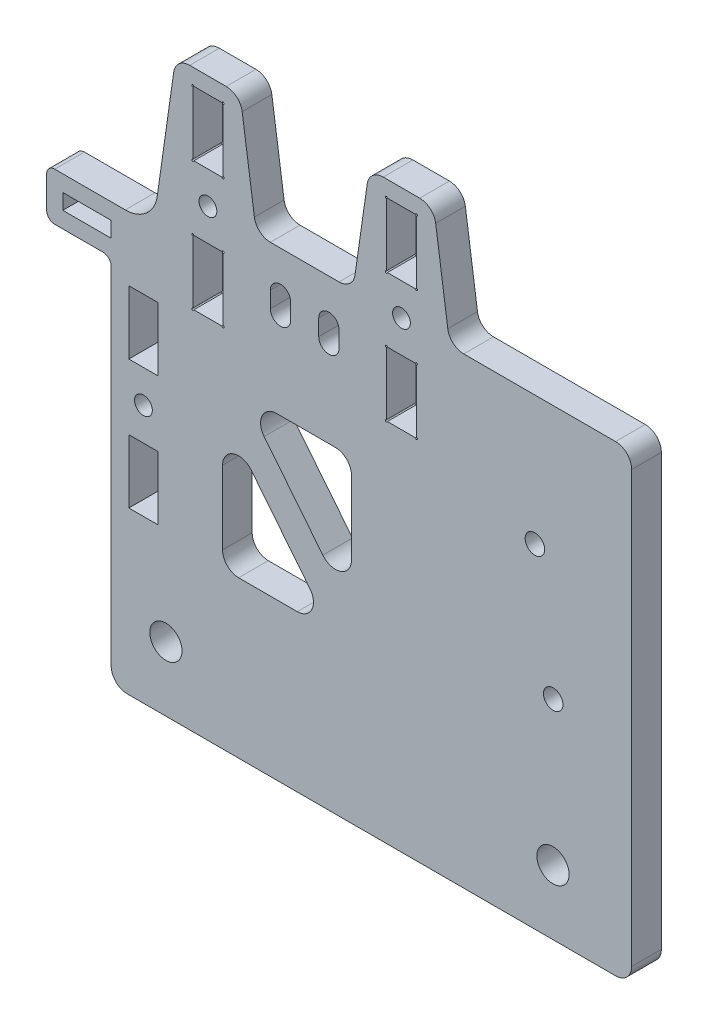
SolidWorks part; units mm, degrees
ref_plane "Front Plane" through (0, 0, 0) normal (0, 0, 1) x (1, 0, 0)
ref_plane "Top Plane" through (0, 0, 0) normal (0, 1, 0) x (1, 0, 0)
ref_plane "Right Plane" through (0, 0, 0) normal (1, 0, 0) x (0, 0, -1)
sketch "Sketch1" plane through (0, 0, 0) normal (0, 0, 1) x (1, 0, 0)
  line L0 (-40.2246, 5.8803) -> (-40.2246, -38.4697) construction
  line L1 (51.8504, -38.4697) -> (-46.5746, -38.4697)
  line L3 (-46.5746, 34.5553) -> (-46.5746, 52.6159)
  line L4 (-46.5746, -38.4697) -> (-46.5746, 34.5553)
  line L5 (51.8504, -38.4697) -> (-46.5746, 34.5553) construction
  line L6 (42.1271, 34.7961) -> (-46.5746, -38.4697) construction
  line L7 (-43.0956, -6.6197) -> (-37.3536, -6.6197)
  line L8 (-43.0956, 18.7803) -> (-37.3536, 18.7803)
  line L9 (-43.0956, 18.7803) -> (-43.0956, 31.2803)
  line L10 (-43.0956, 31.2803) -> (-37.3536, 31.2803)
  line L11 (-37.3536, 18.7803) -> (-37.3536, 31.2803)
  line L12 (-43.0956, 18.7803) -> (-37.3536, 31.2803) construction
  line L13 (-43.0956, 31.2803) -> (-37.3536, 18.7803) construction
  line L14 (-43.0956, -6.6197) -> (-43.0956, 5.8803)
  line L15 (-43.0956, 5.8803) -> (-37.3536, 5.8803)
  line L16 (-37.3536, -6.6197) -> (-37.3536, 5.8803)
  line L17 (-43.0956, -6.6197) -> (-37.3536, 5.8803) construction
  line L18 (-43.0956, 5.8803) -> (-37.3536, -6.6197) construction
  line L19 (-46.5746, 52.6159) -> (51.8504, 52.6159)
  line L20 (51.8504, -25.7697) -> (-46.5746, -25.7697) construction
  line L21 (-40.2246, -0.3697) -> (-40.2246, 25.0303) construction
  line L24 (51.8504, 52.6159) -> (55.8972, 52.6159)
  line L26 (51.8504, -38.4697) -> (55.8972, -38.4697)
  line L27 (55.8972, 52.6159) -> (55.8972, -38.4697)
  circle A0 centre (-35.7968, -25.7697) radius 3.175
  circle A1 centre (40.4032, -25.7697) radius 3.175
  circle A2 centre (-40.2246, 12.3303) radius 1.7526
  point P0 (0, 0)
  point P8 (-40.2246, 25.0303)
  point P14 (-40.2246, -0.3697)
  dimension "D10" = 6.35
  dimension "D13" = 3.5052
  dimension "D1" = 98.425
  dimension "D2" = 73.025
  dimension "D3" = 5.742
  dimension "D4" = 12.5
  dimension "D6" = 6.35
  dimension "D7" = 18.0606
  dimension "D8" = 15.494
  dimension "D12" = 10.7778
  dimension "D5" = 2
  dimension "D11" = 2
extrude "Boss-Extrude1" add sketch "Sketch1" along normal blind 5.842
sketch "Sketch2" plane through (0, 0, 5.842) normal (0, 0, 1) x (1, 0, 0)
  line L0 (55.8972, -38.4697) -> (55.8972, 52.6159) construction
  line L1 (-46.5746, -38.4697) -> (55.8972, -38.4697) construction
  line L2 (33.2912, 44.7153) -> (43.1972, 44.7153) construction
  line L3 (33.2912, -3.5447) -> (43.1972, -3.5447) construction
  line L4 (38.2442, -3.5447) -> (38.2442, 44.7153) construction
  line L6 (48.0747, 0.1423) -> (28.4136, 0.1423)
  line L7 (48.2732, 0.3408) -> (48.2732, 40.8299)
  line L8 (48.0747, 41.0283) -> (28.4136, 41.0283)
  line L9 (28.2152, 0.3408) -> (28.2152, 40.8299)
  line L10 (48.2732, 0.1423) -> (28.2152, 41.0283) construction
  line L11 (48.2732, 41.0283) -> (28.2152, 0.1423) construction
  circle A0 centre (43.1972, -3.5447) radius 1.7526
  circle A1 centre (33.2912, -3.5447) radius 1.7526
  circle A2 centre (43.1972, 44.7153) radius 1.7526
  circle A3 centre (33.2912, 44.7153) radius 1.7526
  arc A4 (48.0747, 0.1423) -> (48.2732, 0.3408) centre (48.2732, 0.1423) ccw
  arc A5 (48.2732, 40.8299) -> (48.0747, 41.0283) centre (48.2732, 41.0283) ccw
  arc A6 (28.2152, 40.8299) -> (28.4136, 41.0283) centre (28.2152, 41.0283) cw
  arc A7 (28.4136, 0.1423) -> (28.2152, 0.3408) centre (28.2152, 0.1423) cw
  point P14 (38.2442, 20.5853)
  dimension "D1" = 3.5052
  dimension "D6" = 0.3969
  dimension "D7" = 0.3969
  dimension "D2" = 12.7
  dimension "D3" = 34.925
  dimension "D4" = 20.058
  dimension "D5" = 40.886
extrude "Cut-Extrude1" [suppressed] cut sketch "Sketch2" against normal through all
sketch "Sketch3" plane through (0, 0, 5.842) normal (0, 0, 1) x (1, 0, 0)
  line L0 (-46.5746, 39.9159) -> (55.8972, 39.9159) construction
  line L1 (-46.5746, 52.6159) -> (-46.5746, -38.4697) construction
  line L2 (55.8972, -38.4697) -> (55.8972, 52.6159) construction
  line L3 (55.8972, 52.6159) -> (-46.5746, 52.6159) construction
  line L4 (7.5909, 46.2659) -> (13.5599, 33.5659) construction
  line L5 (-24.7385, 33.5659) -> (-30.3106, 33.5659)
  line L6 (-24.5401, 33.7644) -> (-24.5401, 46.0675)
  line L7 (-24.7385, 46.2659) -> (-30.3106, 46.2659)
  line L8 (-30.5091, 33.7644) -> (-30.5091, 46.0675)
  line L9 (-24.5401, 33.5659) -> (-30.5091, 46.2659) construction
  line L10 (-8.4746, 52.6159) -> (-8.4746, 39.9159) construction
  line L11 (-24.5401, 46.2659) -> (-30.5091, 33.5659) construction
  line L12 (7.5909, 33.5659) -> (13.5599, 46.2659) construction
  line L13 (13.5599, 33.7644) -> (13.5599, 46.0675)
  line L14 (7.7894, 46.2659) -> (13.3615, 46.2659)
  line L15 (7.5909, 33.7644) -> (7.5909, 46.0675)
  line L16 (7.7894, 33.5659) -> (13.3615, 33.5659)
  arc A0 (-24.7385, 33.5659) -> (-24.5401, 33.7644) centre (-24.5401, 33.5659) ccw
  arc A1 (-30.5091, 33.7644) -> (-30.3106, 33.5659) centre (-30.5091, 33.5659) ccw
  arc A2 (-24.7385, 46.2659) -> (-24.5401, 46.0675) centre (-24.5401, 46.2659) cw
  arc A3 (-30.5091, 46.0675) -> (-30.3106, 46.2659) centre (-30.5091, 46.2659) cw
  arc A4 (13.5599, 46.0675) -> (13.3615, 46.2659) centre (13.5599, 46.2659) ccw
  arc A5 (7.7894, 46.2659) -> (7.5909, 46.0675) centre (7.5909, 46.2659) ccw
  arc A6 (13.5599, 33.7644) -> (13.3615, 33.5659) centre (13.5599, 33.5659) cw
  arc A7 (7.7894, 33.5659) -> (7.5909, 33.7644) centre (7.5909, 33.5659) cw
  point P6 (-27.5246, 39.9159)
  point P7 (-27.5246, 39.9159)
  point P39 (10.5754, 39.9159)
  dimension "D3" = 0.3969
  dimension "D4" = 0.3969
  dimension "D1" = 5.969
  dimension "D2" = 12.7
  dimension "D5" = 12.7
  dimension "D6" = 19.05
  dimension "D9" = 19.05
extrude "Cut-Extrude2" cut sketch "Sketch3" against normal through all
sketch "Sketch4" plane through (0, 0, 5.842) normal (0, 0, 1) x (1, 0, 0)
  line L0 (-30.5091, 39.9159) -> (13.5599, 39.9159) construction
  line L3 (10.5754, 39.9159) -> (10.5754, 65.3159) construction
  line L4 (-8.4746, 39.9159) -> (-8.4746, 46.2659) construction
  line L5 (1.0366, 52.6159) -> (4.2254, 74.8409)
  line L6 (13.3615, 71.6659) -> (7.7894, 71.6659)
  line L7 (13.5599, 71.4675) -> (13.5599, 59.1644)
  line L8 (13.3615, 58.9659) -> (7.7894, 58.9659)
  line L9 (7.5909, 71.4675) -> (7.5909, 59.1644)
  line L10 (13.5599, 71.6659) -> (7.5909, 58.9659) construction
  line L11 (13.5599, 58.9659) -> (7.5909, 71.6659) construction
  line L12 (55.8972, 52.6159) -> (-46.5746, 52.6159) construction
  line L13 (4.2254, 74.8409) -> (16.9254, 74.8409)
  line L14 (16.9254, 74.8409) -> (20.0866, 52.6159)
  line L15 (20.0866, 52.6159) -> (1.0366, 52.6159)
  line L16 (-30.5091, 58.9659) -> (-24.5401, 71.6659) construction
  line L17 (-30.5091, 71.6659) -> (-24.5401, 58.9659) construction
  line L18 (-37.0358, 52.6159) -> (-17.9858, 52.6159)
  line L19 (-33.8746, 74.8409) -> (-37.0358, 52.6159)
  line L20 (-21.1746, 74.8409) -> (-33.8746, 74.8409)
  line L21 (-24.5401, 71.4675) -> (-24.5401, 59.1644)
  line L22 (-30.3106, 58.9659) -> (-24.7385, 58.9659)
  line L23 (-30.5091, 71.4675) -> (-30.5091, 59.1644)
  line L24 (-30.3106, 71.6659) -> (-24.7385, 71.6659)
  line L25 (-17.9858, 52.6159) -> (-21.1746, 74.8409)
  line L26 (13.5599, 33.7644) -> (13.5599, 46.0675) construction
  line L27 (-30.5091, 46.0675) -> (-30.5091, 33.7644) construction
  arc A0 (13.5599, 71.4675) -> (13.3615, 71.6659) centre (13.5599, 71.6659) ccw
  arc A1 (13.3615, 58.9659) -> (13.5599, 59.1644) centre (13.5599, 58.9659) ccw
  arc A2 (7.7894, 58.9659) -> (7.5909, 59.1644) centre (7.5909, 58.9659) cw
  arc A3 (7.5909, 71.4675) -> (7.7894, 71.6659) centre (7.5909, 71.6659) cw
  arc A4 (-24.5401, 71.4675) -> (-24.7385, 71.6659) centre (-24.5401, 71.6659) ccw
  arc A5 (-30.5091, 71.4675) -> (-30.3106, 71.6659) centre (-30.5091, 71.6659) cw
  arc A6 (-24.7385, 58.9659) -> (-24.5401, 59.1644) centre (-24.5401, 58.9659) ccw
  arc A7 (-30.3106, 58.9659) -> (-30.5091, 59.1644) centre (-30.5091, 58.9659) cw
  point P20 (10.5754, 74.8409)
  point P29 (-27.5246, 74.8409)
  dimension "D7" = 0.3969
  dimension "D8" = 0.3969
  dimension "D1" = 25.4
  dimension "D2" = 12.7
  dimension "D3" = 5.969
  dimension "D4" = 9.525
  dimension "D5" = 12.7
  dimension "D6" = 19.05
extrude "Boss-Extrude2" add sketch "Sketch4" against normal up to surface (5.842 mm away) up to face at (10.5754, 39.9159, 0)
fillet "Fillet1" radius 3.175 7 edges at (16.9254, 74.8409, 2.921) (4.2254, 74.8409, 2.921) (-17.9858, 52.6159, 2.921) (-21.1746, 74.8409, 2.921) (-33.8746, 74.8409, 2.921)
sketch "Sketch5" plane through (0, 0, 5.842) normal (0, 0, 1) x (1, 0, 0)
  line L0 (-27.5246, 71.6659) -> (-27.5246, 33.5659) construction
  line L1 (-24.7385, 71.6659) -> (-30.3106, 71.6659) construction
  line L2 (-30.3106, 33.5659) -> (-24.7385, 33.5659) construction
  line L3 (10.5754, 71.6659) -> (10.5754, 33.5659) construction
  line L4 (13.3615, 71.6659) -> (7.7894, 71.6659) construction
  line L5 (7.7894, 33.5659) -> (13.3615, 33.5659) construction
  circle A0 centre (-27.5246, 52.6159) radius 1.7526
  circle A1 centre (10.5754, 52.6159) radius 1.7526
  dimension "D1" = 3.5052
  dimension "D2" = 3.5052
extrude "Cut-Extrude3" cut sketch "Sketch5" against normal through all
sketch "Sketch6" plane through (0, 0, 5.842) normal (0, 0, 1) x (1, 0, 0)
  line L0 (-37.0358, 52.6159) -> (-39.1672, 37.6303)
  line L1 (-34.2626, 72.113) -> (-37.0358, 52.6159) construction
  line L2 (-37.3536, 31.2803) -> (-43.0956, 31.2803) construction
  line L3 (-39.1672, 37.6303) -> (-46.5746, 37.6303)
  line L4 (-46.5746, 52.6159) -> (-46.5746, -38.4697) construction
  line L5 (-46.5746, 37.6303) -> (-46.5746, 52.6159)
  line L6 (-46.5746, 52.6159) -> (-37.0358, 52.6159)
  dimension "D1" = 6.35
extrude "Cut-Extrude4" cut sketch "Sketch6" against normal through all
fillet "Fillet2" radius 3.175 5 edges at (-39.1672, 37.6303, 2.921) (-46.5746, 37.6303, 2.921) (-46.5746, -38.4697, 2.921) (55.8972, 52.6159, 2.921) (55.8972, -38.4697, 2.921)
sketch "Sketch7" [suppressed] plane through (0, 0, 5.842) normal (0, 0, 1) x (1, 0, 0)
  line L0 (6.4764, -22.5947) -> (19.1764, -22.5947) construction
  line L1 (6.4764, -19.4197) -> (19.1764, -19.4197)
  line L2 (6.4764, -25.7697) -> (19.1764, -25.7697)
  line L3 (-43.3996, -38.4697) -> (52.7222, -38.4697) construction
  arc A0 (6.4764, -19.4197) -> (6.4764, -25.7697) centre (6.4764, -22.5947) ccw
  arc A1 (19.1764, -25.7697) -> (19.1764, -19.4197) centre (19.1764, -22.5947) ccw
  point P2 (12.8264, -22.5947)
  dimension "D3" = 3.175
  dimension "D1" = 12.7
  dimension "D2" = 12.7
extrude "Cut-Extrude5" [suppressed] cut sketch "Sketch7" against normal through all
sketch "Sketch8" [suppressed] plane through (0, 0, 5.842) normal (0, 0, 1) x (1, 0, 0)
  line L0 (17.7972, -38.4697) -> (17.7972, 37.7303) construction
  line L1 (-43.3996, -38.4697) -> (52.7222, -38.4697) construction
  line L2 (55.8972, -35.2947) -> (55.8972, 49.4409) construction
  line L3 (14.6222, 5.9803) -> (20.9722, 5.9803) construction
  line L4 (14.6222, 7.5678) -> (20.9722, 7.5678)
  line L5 (14.6222, 4.3928) -> (20.9722, 4.3928)
  line L6 (14.6222, 25.0303) -> (20.9722, 25.0303) construction
  line L7 (14.6222, 26.6178) -> (20.9722, 26.6178)
  line L8 (14.6222, 23.4428) -> (20.9722, 23.4428)
  arc A0 (14.6222, 7.5678) -> (14.6222, 4.3928) centre (14.6222, 5.9803) ccw
  arc A1 (20.9722, 4.3928) -> (20.9722, 7.5678) centre (20.9722, 5.9803) ccw
  arc A2 (14.6222, 26.6178) -> (14.6222, 23.4428) centre (14.6222, 25.0303) ccw
  arc A3 (20.9722, 23.4428) -> (20.9722, 26.6178) centre (20.9722, 25.0303) ccw
  point P8 (17.7972, 5.9803)
  point P17 (17.7972, 25.0303)
  dimension "D2" = 1.5875
  dimension "D1" = 38.1
  dimension "D3" = 6.35
  dimension "D4" = 76.2
  dimension "D5" = 2
  dimension "D6" = 44.45
extrude "Cut-Extrude6" [suppressed] cut sketch "Sketch8" against normal through all
sketch "Sketch9" [suppressed] plane through (0, 0, 5.842) normal (0, 0, 1) x (1, 0, 0)
  line L0 (3.3014, -22.5947) -> (-46.5746, -22.5947) construction
  line L1 (-46.5746, 34.4553) -> (-46.5746, -35.2947) construction
  line L2 (-15.7486, -25.7697) -> (-15.7486, -19.4197) construction
  line L3 (-17.3361, -25.7697) -> (-17.3361, -19.4197)
  line L4 (-14.1611, -25.7697) -> (-14.1611, -19.4197)
  line L5 (-3.0486, -25.7697) -> (-3.0486, -19.4197) construction
  line L6 (-4.6361, -25.7697) -> (-4.6361, -19.4197)
  line L7 (-1.4611, -25.7697) -> (-1.4611, -19.4197)
  arc A0 (6.4764, -19.4197) -> (6.4764, -25.7697) centre (6.4764, -22.5947) ccw construction
  arc A1 (-17.3361, -25.7697) -> (-14.1611, -25.7697) centre (-15.7486, -25.7697) ccw
  arc A2 (-14.1611, -19.4197) -> (-17.3361, -19.4197) centre (-15.7486, -19.4197) ccw
  arc A3 (-4.6361, -25.7697) -> (-1.4611, -25.7697) centre (-3.0486, -25.7697) ccw
  arc A4 (-1.4611, -19.4197) -> (-4.6361, -19.4197) centre (-3.0486, -19.4197) ccw
  point P10 (-15.7486, -22.5947)
  point P18 (-3.0486, -22.5947)
  dimension "D2" = 1.5875
  dimension "D1" = 6.35
  dimension "D3" = 19.05
extrude "Cut-Extrude7" [suppressed] cut sketch "Sketch9" against normal through all
sketch "Sketch10" plane through (0, 0, 5.842) normal (0, 0, 1) x (1, 0, 0)
  line L0 (-20.5876, 24.0409) -> (0.7464, 24.0409)
  line L1 (-30.3106, 33.5659) -> (-24.7385, 33.5659) construction
  line L2 (-24.6536, 18.9584) -> (-24.6536, -7.7091)
  line L3 (-37.3536, 18.7803) -> (-37.3536, 31.2803) construction
  line L4 (0.7464, 24.0409) -> (0.7464, -2.6266)
  line L5 (-3.3196, -7.7091) -> (-24.6536, -7.7091)
  line L7 (-24.6536, 18.9584) -> (-3.3196, -7.7091)
  line L8 (-20.5876, 24.0409) -> (0.7464, -2.6266)
  dimension "D1" = 9.525
  dimension "D2" = 12.7
extrude "Cut-Extrude8" cut sketch "Sketch10" against normal through all
fillet "Fillet3" radius 3.175 6 edges at (0.7464, 24.0409, 2.921) (0.7464, -2.6266, 2.921) (-20.5876, 24.0409, 2.921) (-24.6536, 18.9584, 2.921) (-24.6536, -7.7091, 2.921) (-3.3196, -7.7091, 2.921)
sketch "Sketch11" plane through (0, 0, 5.842) normal (0, 0, 1) x (1, 0, 0)
  line L0 (55.8972, -35.2947) -> (55.8972, 49.4409) construction
  line L1 (52.7222, 52.6159) -> (22.842, 52.6159) construction
  circle A0 centre (36.8472, 27.2159) radius 1.92
  circle A1 centre (40.4472, 2.5659) radius 1.92
  dimension "D1" = 3.84
  dimension "D2" = 3.84
  dimension "D3" = 3.6
  dimension "D4" = 24.65
  dimension "D5" = 19.05
  dimension "D6" = 25.4
extrude "Cut-Extrude9" cut sketch "Sketch11" against normal through all
sketch "Sketch12" plane through (0, 0, 5.842) normal (0, 0, 1) x (1, 0, 0)
  line L0 (-24.5401, 42.8787) -> (7.5909, 42.8787) construction
  line L1 (-24.5401, 33.7644) -> (-24.5401, 46.0675) construction
  line L2 (7.5909, 46.0675) -> (7.5909, 33.7644) construction
  line L3 (-8.4746, 52.6159) -> (-8.4746, 42.8787) construction
  line L4 (-1.7153, 52.6159) -> (-15.2338, 52.6159) construction
  line L5 (-3.7121, 41.2912) -> (-3.7121, 44.4662) construction
  line L6 (-5.7121, 41.2912) -> (-5.7121, 44.4662)
  line L7 (-1.7121, 41.2912) -> (-1.7121, 44.4662)
  line L8 (-13.2371, 41.2912) -> (-13.2371, 44.4662) construction
  line L9 (-11.2371, 41.2912) -> (-11.2371, 44.4662)
  line L10 (-15.2371, 41.2912) -> (-15.2371, 44.4662)
  arc A0 (-5.7121, 41.2912) -> (-1.7121, 41.2912) centre (-3.7121, 41.2912) ccw
  arc A1 (-1.7121, 44.4662) -> (-5.7121, 44.4662) centre (-3.7121, 44.4662) ccw
  arc A2 (-11.2371, 41.2912) -> (-15.2371, 41.2912) centre (-13.2371, 41.2912) cw
  arc A3 (-15.2371, 44.4662) -> (-11.2371, 44.4662) centre (-13.2371, 44.4662) cw
  point P12 (-3.7121, 42.8787)
  point P19 (-13.2371, 42.8787)
  dimension "D2" = 2
  dimension "D1" = 3.175
  dimension "D3" = 4.7625
extrude "Cut-Extrude10" cut sketch "Sketch12" against normal through all
sketch "Sketch14" plane through (0, 0, 5.842) normal (0, 0, 1) x (1, 0, 0)
  line L0 (-46.5746, 37.6303) -> (-55.1563, 37.6303) construction
  line L1 (-43.3996, 37.6303) -> (-41.9226, 37.6303) construction
  line L2 (-46.5746, 34.4553) -> (-46.5746, -35.2947) construction
  line L3 (-46.5746, 37.6303) -> (-56.0996, 37.6303)
  line L4 (-42.6611, 37.6303) -> (-42.6611, 34.4553)
  line L5 (-42.6611, 34.4553) -> (-59.2746, 34.4553)
  line L6 (-59.2746, 37.6303) -> (-59.2746, 34.4553)
  line L7 (-59.2746, 37.6303) -> (-59.2746, 43.8533)
  line L8 (-46.5746, 40.6783) -> (-56.0996, 40.6783)
  line L9 (-46.5746, 40.6783) -> (-46.5746, 37.6303)
  line L10 (-46.5746, 37.6303) -> (-56.0996, 37.6303) construction
  line L11 (-56.0996, 40.6783) -> (-56.0996, 37.6303)
  line L12 (-46.5746, 40.6783) -> (-56.0996, 37.6303) construction
  line L13 (-46.5746, 37.6303) -> (-56.0996, 40.6783) construction
  line L14 (-59.2746, 43.8533) -> (-38.2821, 43.8533)
  line L15 (-34.2626, 72.113) -> (-38.7792, 40.3582) construction
  line L16 (-42.6611, 37.6303) -> (-41.9226, 37.6303)
  line L17 (-38.2821, 43.8533) -> (-38.7792, 40.3582)
  arc A0 (-41.9226, 37.6303) -> (-38.7792, 40.3582) centre (-41.9226, 40.8053) ccw construction
  arc A1 (-41.9226, 37.6303) -> (-38.7792, 40.3582) centre (-41.9226, 40.8053) ccw
  point P9 (-51.3371, 39.1543)
  dimension "D1" = 3.175
  dimension "D2" = 12.7
  dimension "D3" = 3.048
  dimension "D4" = 9.525
  dimension "D5" = 3.175
  dimension "D6" = 3.175
extrude "Boss-Extrude3" add sketch "Sketch14" against normal up to surface (5.842 mm away)
fillet "Fillet4" radius 1.5875 3 edges at (-59.2746, 43.8533, 2.921) (-59.2746, 34.4553, 2.921) (-46.5746, 34.4553, 2.921)
fillet "Fillet5" radius 6.35 1 edges at (-38.2821, 43.8533, 2.921)
